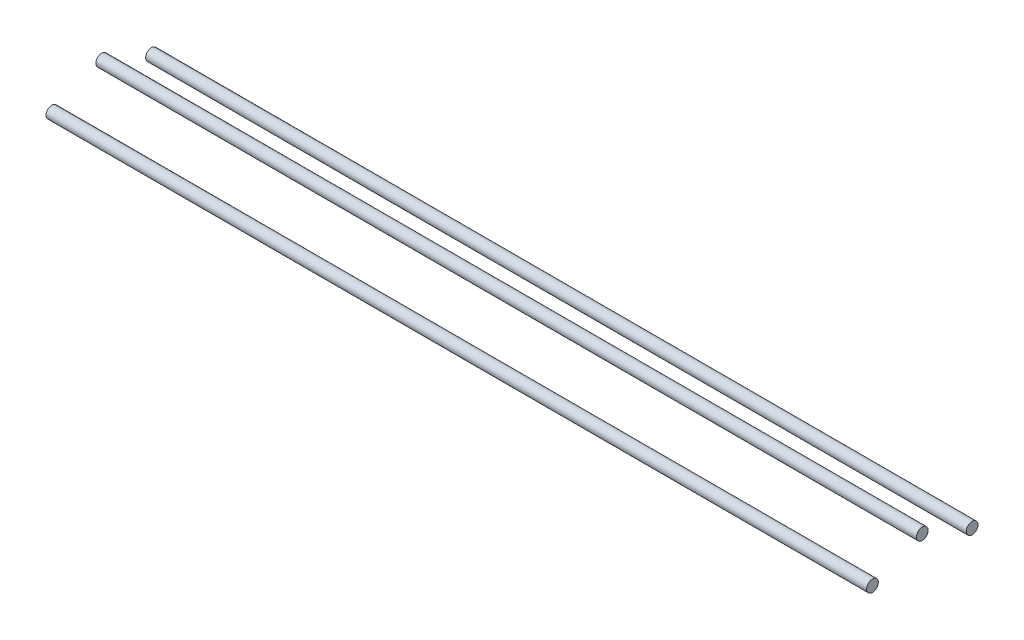
SolidWorks part; units mm, degrees
material "5052-H32"
ref_plane "Front Plane" through (0, 0, 0) normal (0, 0, 1) x (1, 0, 0)
ref_plane "Top Plane" through (0, 0, 0) normal (0, 1, 0) x (1, 0, 0)
ref_plane "Right Plane" through (0, 0, 0) normal (1, 0, 0) x (0, 0, -1)
sketch "Sketch2" plane through (0, 0, 0) normal (1, 0, 0) x (0, 0, -1)
  circle A0 centre (25.5, 0) radius 3 construction
  circle A1 centre (0, 10.2672) radius 3 construction
  circle A2 centre (-25.5, 0) radius 3 construction
  circle A3 centre (25.5, 0) radius 3
  circle A4 centre (0, 10.2672) radius 3
  circle A5 centre (-25.5, 0) radius 3
extrude "Boss-Extrude1" add sketch "Sketch2" against normal up to vertex (410 mm away) from vertex at 10
